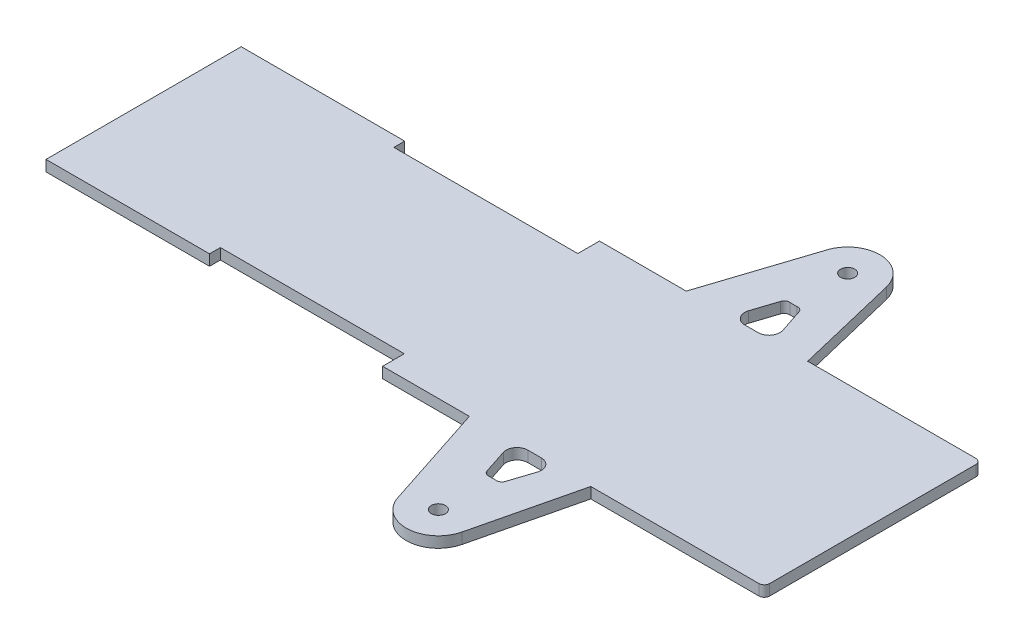
SolidWorks part; units mm, degrees
ref_plane "Front Plane" through (0, 0, 0) normal (0, 0, 1) x (1, 0, 0)
ref_plane "Top Plane" through (0, 0, 0) normal (0, 1, 0) x (1, 0, 0)
ref_plane "Right Plane" through (0, 0, 0) normal (1, 0, 0) x (0, 0, -1)
sketch "Sketch1" plane through (0, 0, 0) normal (0, 1, 0) x (1, 0, 0)
  line L0 (-64.5699, 0) -> (82.804, 0) construction
  line L1 (26.924, -25.4) -> (-26.924, -25.4)
  line L2 (71.424, -59.917) -> (71.424, 59.917) construction
  line L3 (26.924, 25.4) -> (-26.924, 25.4)
  line L4 (26.924, 25.4) -> (26.924, 31.75)
  line L5 (26.924, -25.4) -> (-26.924, 25.4) construction
  line L6 (26.924, 25.4) -> (-26.924, -25.4) construction
  line L7 (-26.924, 25.4) -> (-26.924, 28.575)
  line L8 (-46.228, -28.575) -> (-26.924, -28.575)
  line L10 (-46.228, 28.575) -> (-26.924, 28.575)
  line L11 (-26.924, -28.575) -> (-26.924, -25.4)
  line L12 (-46.228, -28.575) -> (-26.924, 28.575) construction
  line L13 (-46.228, 28.575) -> (-26.924, -28.575) construction
  line L14 (52.324, -31.75) -> (26.924, -31.75)
  line L15 (138.684, -31.75) -> (138.684, 31.75)
  line L16 (138.684, 31.75) -> (87.884, 31.75)
  line L17 (26.924, -31.75) -> (26.924, -25.4)
  line L18 (138.684, -31.75) -> (26.924, 31.75) construction
  line L19 (138.684, 31.75) -> (26.924, -31.75) construction
  line L20 (52.324, 31.75) -> (62.6076, 63.2401)
  line L21 (52.324, -31.75) -> (62.6076, -63.2401)
  line L22 (52.324, 31.75) -> (26.924, 31.75)
  line L23 (87.884, 31.75) -> (80.5851, 62.1188)
  line L24 (138.684, -31.75) -> (87.884, -31.75)
  line L25 (87.884, -31.75) -> (80.5851, -62.1188)
  line L26 (77.774, 31.75) -> (65.074, 31.75)
  line L27 (65.074, 31.75) -> (69.142, 44.2069)
  line L28 (77.774, 31.75) -> (73.706, 44.2069)
  line L29 (77.774, -31.75) -> (73.706, -44.2069)
  line L30 (65.074, -31.75) -> (69.142, -44.2069)
  line L31 (77.774, -31.75) -> (65.074, -31.75)
  line L32 (-36.449, -44.45) -> (-36.449, 44.45) construction
  line L34 (-74.803, -28.575) -> (-46.228, -28.575)
  line L35 (-74.803, -28.575) -> (-74.803, 28.575)
  line L36 (-74.803, 28.575) -> (-46.228, 28.575)
  line L38 (-74.803, -28.575) -> (-46.228, 28.575) construction
  line L39 (-74.803, 28.575) -> (-46.228, -28.575) construction
  circle A0 centre (71.424, 59.917) radius 2.0828
  arc A1 (80.5851, 62.1188) -> (62.6076, 63.2401) centre (71.424, 59.917) ccw
  arc A2 (80.5851, -62.1188) -> (62.6076, -63.2401) centre (71.424, -59.917) cw
  arc A3 (69.142, -44.2069) -> (73.706, -44.2069) centre (71.424, -59.917) cw
  arc A4 (69.142, 44.2069) -> (73.706, 44.2069) centre (71.424, 59.917) ccw
  circle A6 centre (71.424, -59.917) radius 2.0828
  point P0 (0, 0)
  point P8 (-36.576, 0)
  point P20 (71.424, 0)
  point P31 (138.684, 0)
  point P37 (71.424, 31.75)
  point P42 (71.424, -31.75)
  point P43 (-60.5155, 0)
  point P46 (-36.449, 0)
  dimension "D9" = 4.1656
  dimension "D10" = 50.8
  dimension "D13" = 9.525
  dimension "D15" = 15.875
  dimension "D16" = 28.575
  dimension "D1" = 53.848
  dimension "D2" = 50.8
  dimension "D3" = 57.15
  dimension "D4" = 19.304
  dimension "D5" = 111.76
  dimension "D6" = 63.5
  dimension "D7" = 119.834
  dimension "D8" = 44.5
  dimension "D11" = 25.4
  dimension "D12" = 63.5
  dimension "D14" = 12.7
  dimension "D17" = 88.9
extrude "Boss-Extrude1" add sketch "Sketch1" along normal blind 3.175
fillet "Fillet1" radius 1.5875 4 edges at (73.706, 1.5875, -44.2069) (69.142, 1.5875, -44.2069) (73.706, 1.5875, 44.2069) (69.142, 1.5875, 44.2069)
fillet "Fillet2" radius 3.175 4 edges at (77.774, 1.5875, 31.75) (65.074, 1.5875, 31.75) (77.774, 1.5875, -31.75) (65.074, 1.5875, -31.75)
fillet "Fillet3" radius 1.5875 2 edges at (138.684, 1.5875, -31.75) (138.684, 1.5875, 31.75)
